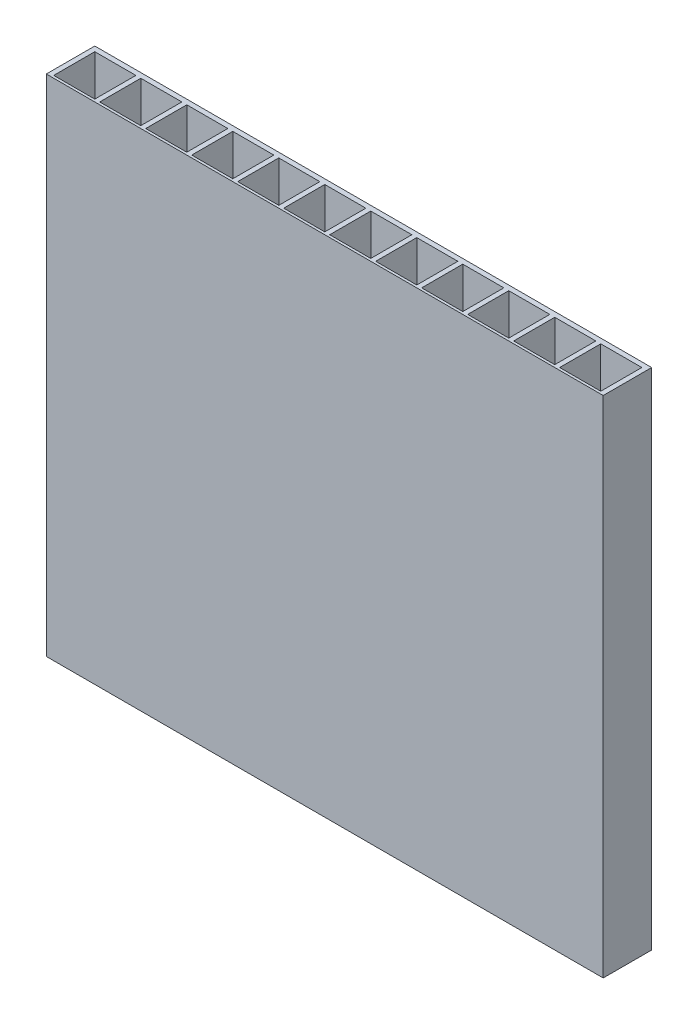
SolidWorks part; units mm, degrees
ref_plane "Front Plane" through (0, 0, 0) normal (0, 0, 1) x (1, 0, 0)
ref_plane "Top Plane" through (0, 0, 0) normal (0, 1, 0) x (1, 0, 0)
ref_plane "Right Plane" through (0, 0, 0) normal (1, 0, 0) x (0, 0, -1)
sketch "Sketch1" plane through (0, 0, 0) normal (0, 1, 0) x (1, 0, 0)
  line L1 (-3.175, -3.175) -> (3.175, -3.175)
  line L2 (-3.175, -3.175) -> (-3.175, 3.175)
  line L3 (-3.175, 3.175) -> (3.175, 3.175)
  line L4 (3.175, -3.175) -> (3.175, 3.175)
  line L5 (-3.175, -3.175) -> (3.175, 3.175) construction
  line L6 (-3.175, 3.175) -> (3.175, -3.175) construction
  line L7 (-3.937, -3.937) -> (3.937, -3.937)
  line L8 (-3.937, -3.937) -> (-3.937, 3.937)
  line L9 (-3.937, 3.937) -> (3.937, 3.937)
  line L10 (3.937, -3.937) -> (3.937, 3.937)
  line L11 (-3.937, -3.937) -> (3.937, 3.937) construction
  line L12 (-3.937, 3.937) -> (3.937, -3.937) construction
  point P0 (0, 0)
  point P6 (0, 0)
  dimension "D1" = 0.762
  dimension "D2" = 6.35
extrude "Boss-Extrude1" add sketch "Sketch1" along normal blind 78
pattern_linear "LPattern1" count 12 spacing 7.112 along (1, 0, 0) of "Boss-Extrude1"
sketch "Sketch3" plane through (0, 0, 0) normal (0, 0, 1) x (1, 0, 0)
  line L4 (82.169, 0) -> (82.169, 78)
  line L5 (82.169, 78) -> (-3.937, 78)
  line L6 (-3.937, 78) -> (-3.937, 0)
  line L7 (-3.937, 0) -> (82.169, 0)
  line L9 (82.169, 78) -> (-3.937, 78)
  line L10 (-3.937, 78) -> (-3.937, 0)
  line L11 (-3.937, 0) -> (82.169, 0)
  line L13 (82.169, 0) -> (82.169, 78)
  dimension "D1" = 0
extrude "Cut-Extrude1" cut sketch "Sketch3" against normal offset from surface (0.381 mm away) 0.381 from surface at 3.937 up to face at (0, 39, 3.175) starting at face at (39.116, 39, 3.937)
equation "\"column_diameter\"=0.25"
equation "\"D2@Sketch1\"=\"column_diameter\""
equation "\"wall_thickness\"= 0.03"
equation "\"D1@Sketch1\"=\"wall_thickness\""
equation "\"D3@LPattern1\"=\"column_diameter\"+\"wall_thickness\""
equation "\"thin_wall_thickness\"= 0.015"
equation "\"D1@Cut-Extrude1\"=\"thin_wall_thickness\""
equation "\"num_slots\"= 12"
equation "\"column_height\"= ( \"num_slots\" + 1 ) * 6mm"
equation "\"D1@Boss-Extrude1\"=\"column_height\""
equation "\"D1@LPattern1\"=\"num_slots\""
